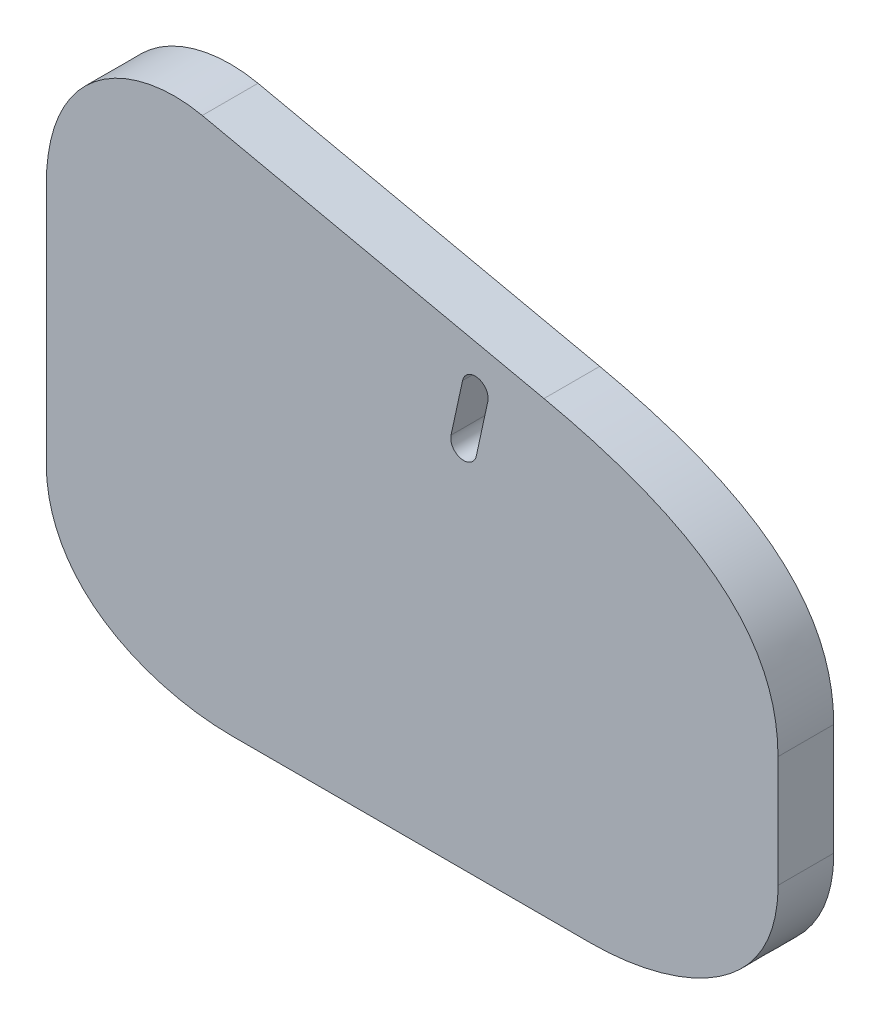
SolidWorks part; units mm, degrees
ref_plane "Спереди" through (0, 0, 0) normal (0, 0, 1) x (1, 0, 0)
ref_plane "Сверху" through (0, 0, 0) normal (0, 1, 0) x (1, 0, 0)
ref_plane "Справа" through (0, 0, 0) normal (1, 0, 0) x (0, 0, -1)
sketch "Эскиз1_fr" plane through (0, 0, 0) normal (0, 0, 1) x (1, 0, 0)
  line L0 (0, 0) -> (0, 20)
  line L1 (-41.9869, 54.6497) -> (-103.3012, 67.9789)
  line L2 (-131.2925, 43.0977) -> (-131.2925, 0)
  line L3 (-33.5451, -25.7698) -> (-97.9695, -25.7698)
  line L4 (-54.3328, 49.6459) -> (-56.3993, 40.1399)
  line L5 (-54.3328, 49.6459) -> (-56.3993, 40.1399) construction
  line L6 (-52.0671, 49.1533) -> (-54.1336, 39.6474)
  line L7 (-56.5986, 50.1384) -> (-58.6651, 40.6325)
  arc A0 (-52.0671, 49.1533) -> (-56.5986, 50.1384) centre (-54.3328, 49.6459) ccw
  arc A1 (-58.6651, 40.6325) -> (-54.1336, 39.6474) centre (-56.3993, 40.1399) ccw
  spline S0 degree 3 poles (0, 20) (0, 38.146) (-14.2095, 48.6111) (-41.9869, 54.6497) knots 0 0 0 0 1 1 1 1
  spline S1 degree 3 poles (-103.3012, 67.9789) (-115.5, 70.6308) (-131.2925, 63.3933) (-131.2925, 43.0977) knots 0 0 0 0 1 1 1 1
  spline S2 degree 3 poles (-33.5451, -25.7698) (-19.4449, -25.7698) (0, -19.0638) (0, 0) knots 0 0 0 0 1 1 1 1
  spline S3 degree 3 poles (-97.9695, -25.7698) (-112.0112, -25.7698) (-131.2925, -19.0252) (-131.2925, 0) knots 0 0 0 0 1 1 1 1
  point P11 (-55.3661, 44.8929)
  dimension "D1" = 20
extrude "Бобышка-Вытянуть1" add sketch "Эскиз1_fr" along normal blind 10 contours S3 L3 S2 L0 S0 L1 S1 L2 A1 L7 A0 L6
